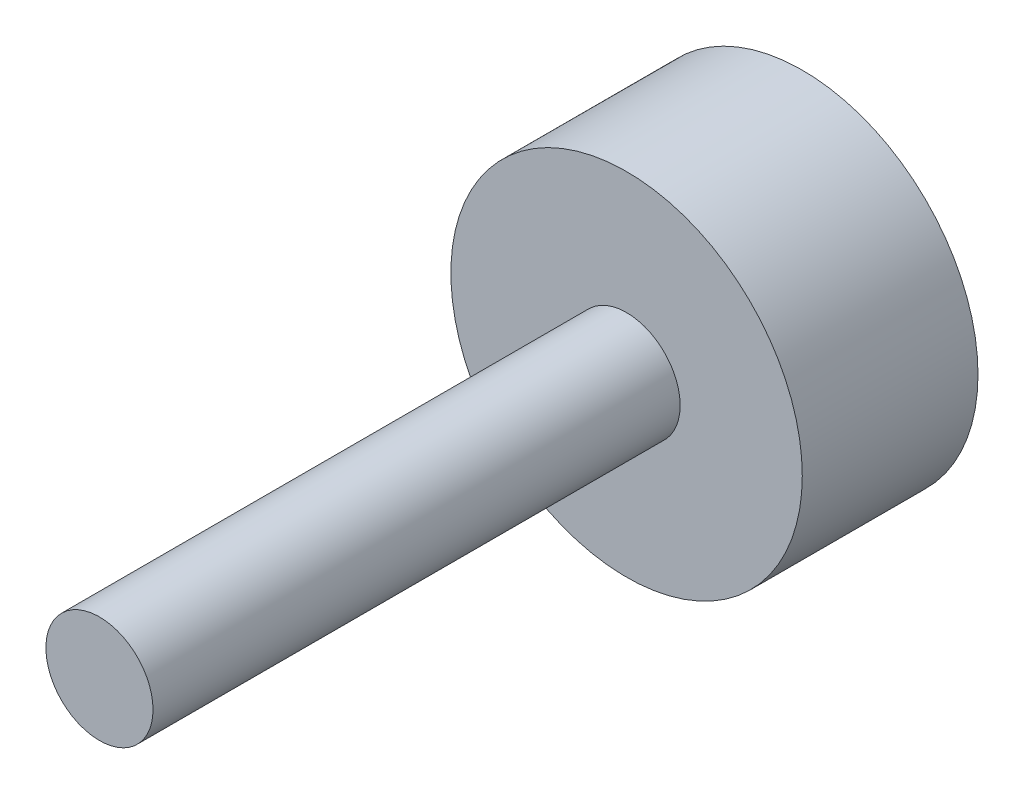
SolidWorks part; units mm, degrees
material "Cast Alloy Steel"
ref_plane "Front Plane" through (0, 0, 0) normal (0, 0, 1) x (1, 0, 0)
ref_plane "Top Plane" through (0, 0, 0) normal (0, 1, 0) x (1, 0, 0)
ref_plane "Right Plane" through (0, 0, 0) normal (1, 0, 0) x (0, 0, -1)
sketch "Sketch1" plane through (0, 0, 0) normal (0, 0, 1) x (1, 0, 0)
  circle A0 centre (0, 0) radius 5
  dimension "D1" = 10
extrude "Boss-Extrude1" add sketch "Sketch1" along normal blind 5
sketch "Sketch2" plane through (0, 0, 5) normal (0, 0, 1) x (1, 0, 0)
  circle A0 centre (0, 0) radius 1.524
  dimension "D1" = 3.048
extrude "Boss-Extrude2" add sketch "Sketch2" along normal blind 15
